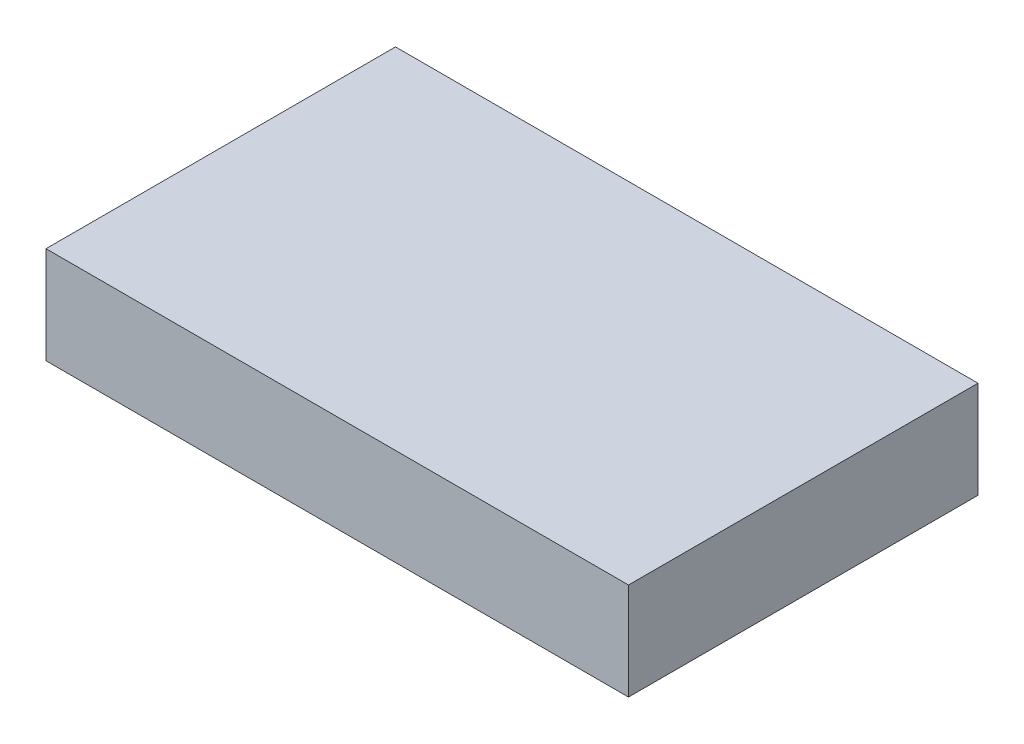
SolidWorks part; units mm, degrees
ref_plane "前视基准面" through (0, 0, 0) normal (0, 0, 1) x (1, 0, 0)
ref_plane "上视基准面" through (0, 0, 0) normal (0, 1, 0) x (1, 0, 0)
ref_plane "右视基准面" through (0, 0, 0) normal (1, 0, 0) x (0, 0, -1)
sketch "草图1" plane through (0, 0, 0) normal (0, 1, 0) x (1, 0, 0)
  line L1 (0, 0) -> (30, 0)
  line L2 (0, 0) -> (0, -18)
  line L3 (0, -18) -> (30, -18)
  line L4 (30, 0) -> (30, -18)
  dimension "D1" = 30
  dimension "D2" = 18
extrude "凸台-拉伸1" add sketch "草图1" along normal blind 5
